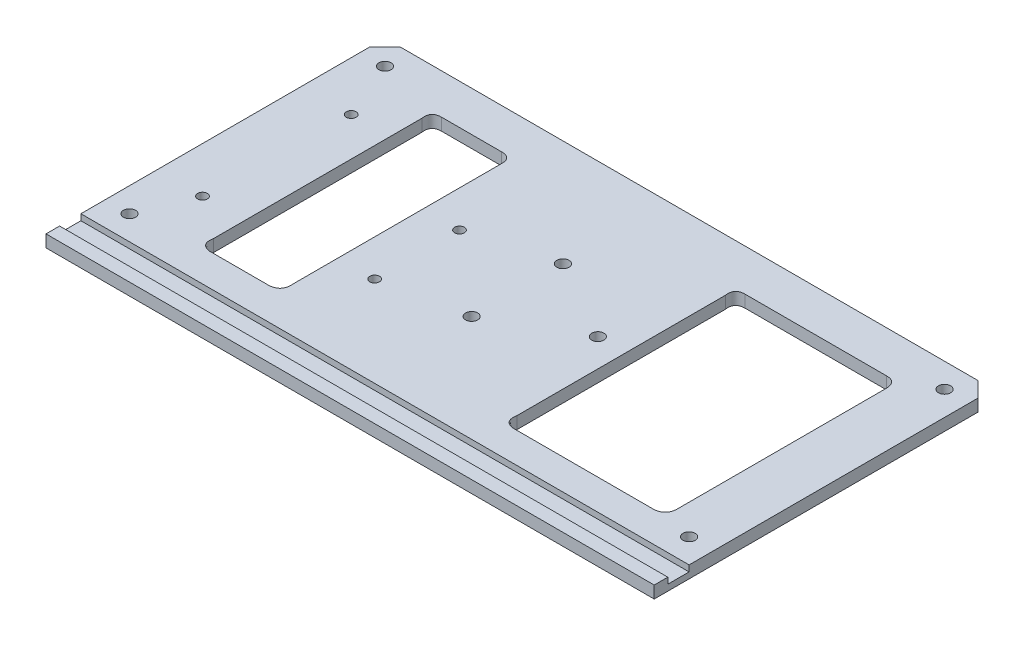
SolidWorks part; units mm, degrees
ref_plane "Plan de face" through (0, 0, 0) normal (0, 0, 1) x (1, 0, 0)
ref_plane "Plan de dessus" through (0, 0, 0) normal (0, 1, 0) x (1, 0, 0)
ref_plane "Plan de droite" through (0, 0, 0) normal (1, 0, 0) x (0, 0, -1)
sketch "Esquisse1" plane through (0, 0, 0) normal (0, 1, 0) x (1, 0, 0)
  line L0 (-100, 50) -> (100, 50)
  line L1 (0, -55) -> (0, 55) construction
  line L2 (-100, 50) -> (-100, -50)
  line L3 (-55, 0) -> (55, 0) construction
  line L4 (100, 50) -> (100, -50)
  line L5 (-100, -50) -> (100, -50)
  circle A0 centre (-92, 42) radius 2
  circle A1 centre (92, 42) radius 2
  circle A2 centre (92, -42) radius 2
  circle A3 centre (-92, -42) radius 2
  circle A4 centre (-6.5, -15) radius 2
  circle A5 centre (20, 0) radius 2
  circle A6 centre (-6.5, 15) radius 2
  circle A7 centre (-33.1, -20.3) radius 1.6
  circle A8 centre (-33.1, 7.6) radius 1.6
  circle A9 centre (-85, -25) radius 1.6
  circle A10 centre (-83.8, 22.7) radius 1.6
  point P5 (0, -50)
  point P9 (0, 50)
  point P10 (100, 0)
  point P11 (-100, 0)
  dimension "D3" = 4
  dimension "D6" = 4
  dimension "D9" = 4
  dimension "D11" = 3.2
  dimension "D1" = 200
  dimension "D2" = 100
  dimension "D4" = 8
  dimension "D5" = 8
  dimension "D7" = 15
  dimension "D8" = 6.5
  dimension "D10" = 20
  dimension "D12" = 4.7
  dimension "D13" = 51.9
  dimension "D14" = 4.7
  dimension "D15" = 50.7
  dimension "D16" = 15.1
  dimension "D17" = 27.9
  dimension "D18" = 15
  dimension "D19" = 25
extrude "Boss.-Extru.1" add sketch "Esquisse1" along normal blind 4
sketch "Esquisse2" plane through (0, 4, 0) normal (0, 1, 0) x (1, 0, 0)
  line L0 (-71.124, 33.2673) -> (-71.124, -35.2629)
  line L1 (-45.1192, 33.2673) -> (-45.1192, -35.2629)
  line L2 (-68.1799, 36.799) -> (-48.4126, 36.799)
  line L3 (-68.1799, -39.5032) -> (-48.4126, -39.5032)
  line L4 (29.1856, 32.7694) -> (29.1856, -35.7609)
  line L5 (82.1381, 32.7694) -> (82.1381, -35.7609)
  line L6 (32.1297, 36.301) -> (78.6558, 36.301)
  line L7 (32.1297, -40.0012) -> (78.6558, -40.0012)
  spline S0 degree 2 poles (-48.4126, 36.799) (-44.9878, 36.7848) (-45.1192, 33.2673) knots 0 0 0 1 1 1
  spline S1 degree 2 poles (-68.1799, 36.799) (-71.6257, 36.7837) (-71.124, 33.2673) knots 0 0 0 1 1 1
  spline S2 degree 2 poles (-71.124, -35.2629) (-71.8081, -39.0256) (-68.1799, -39.5032) knots 0 0 0 1 1 1
  spline S3 degree 2 poles (-45.1192, -35.2629) (-44.7973, -39.0381) (-48.4126, -39.5032) knots 0 0 0 1 1 1
  spline S4 degree 2 poles (78.6558, 36.301) (82.0348, 36.2515) (82.1381, 32.7694) knots 0 0 0 1 1 1
  spline S5 degree 2 poles (32.1297, 36.301) (28.6839, 36.2857) (29.1856, 32.7694) knots 0 0 0 1 1 1
  spline S6 degree 2 poles (29.1856, -35.7609) (28.5015, -39.5236) (32.1297, -40.0012) knots 0 0 0 1 1 1
  spline S7 degree 2 poles (82.1381, -35.7609) (82.2214, -39.5042) (78.6558, -40.0012) knots 0 0 0 1 1 1
extrude "Enlèv. mat.-Extru.1" cut sketch "Esquisse2" against normal blind 10
sketch "Esquisse3" plane through (0, 0, 0) normal (0, -1, 0) x (1, 0, 0)
  line L0 (-100, 50) -> (-100, 61.4713)
  line L1 (-100, 61.4713) -> (0, 61.4713)
  line L2 (-100, 50) -> (100, 50)
  line L3 (100, 50) -> (100, 61.4713)
  line L4 (100, 61.4713) -> (0, 61.4713)
extrude "Boss.-Extru.2" add sketch "Esquisse3" against normal blind 2
sketch "Esquisse4" plane through (0, 2, 0) normal (0, 1, 0) x (1, 0, 0)
  line L0 (-100, -61.4713) -> (-100, -57)
  line L1 (-100, -61.4713) -> (-100, -50) construction
  line L2 (-100, -57) -> (100, -57)
  line L3 (100, -50) -> (100, -61.4713) construction
  line L4 (100, -57) -> (100, -61.4713)
  line L5 (100, -61.4713) -> (-100, -61.4713)
  line L6 (-100, -57) -> (-100, -61.4713)
  line L7 (-100, -50) -> (100, -50) construction
  line M3 (-100, -50) -> (-100, -61.4713)
  line M4 (-100, -61.4713) -> (100, -61.4713)
  line M5 (100, -61.4713) -> (100, -50)
  dimension "D1" = 7
extrude "Boss.-Extru.3" add sketch "Esquisse4" along normal blind 2 contours L2 M3 M4 M5
chamfer "Chanfrein1" distance 5 angle 45 2 edges at (100, 2, -50) (-100, 2, -50)
